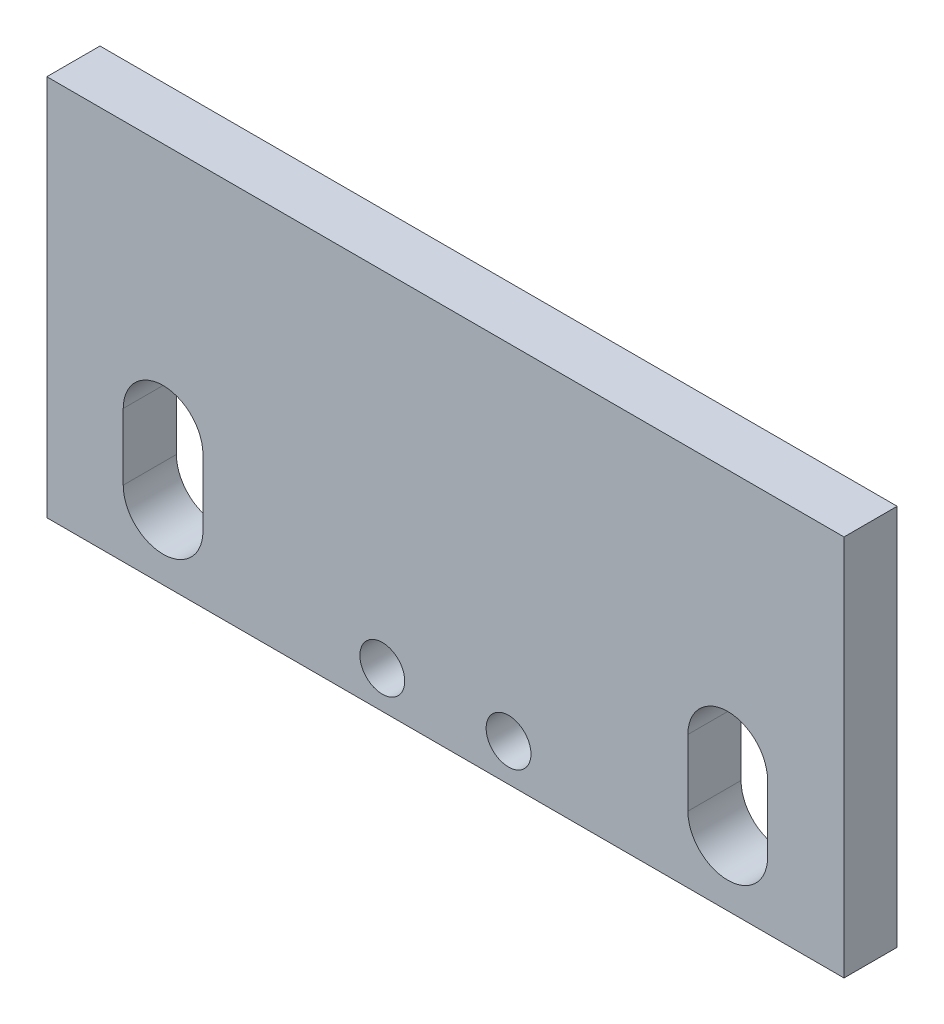
SolidWorks part; units mm, degrees
ref_plane "Front Plane" through (0, 0, 0) normal (0, 0, 1) x (1, 0, 0)
ref_plane "Top Plane" through (0, 0, 0) normal (0, 1, 0) x (1, 0, 0)
ref_plane "Right Plane" through (0, 0, 0) normal (1, 0, 0) x (0, 0, -1)
sketch "Sketch2" plane through (0, 0, 0) normal (0, 0, 1) x (1, 0, 0)
  line L0 (-0.0058, 0.0349) -> (7.9941, 0.0349) construction
  line L1 (7.9941, 0.0349) -> (7.9941, 12.5349) construction
  line L2 (-0.0058, 0.0349) -> (-0.0058, 12.5349) construction
  line L3 (-0.0058, 12.5349) -> (7.9941, 12.5349) construction
  line L4 (3.9941, 11.5349) -> (3.9941, 0.0349) construction
  line L5 (-8.0058, 11.5349) -> (15.9941, 11.5349)
  line L6 (-8.0058, 11.5349) -> (-8.0058, 0.0349)
  line L7 (-8.0058, 0.0349) -> (15.9941, 0.0349)
  line L8 (15.9941, 11.5349) -> (15.9941, 0.0349)
  line L9 (12.4941, 2.0349) -> (12.4941, 4.0349) construction
  line L10 (11.2941, 2.0349) -> (11.2941, 4.0349)
  line L11 (13.6941, 2.0349) -> (13.6941, 4.0349)
  line L12 (-4.5058, 2.0349) -> (-4.5058, 4.0349) construction
  line L13 (-3.3058, 2.0349) -> (-3.3058, 4.0349)
  line L14 (-5.7058, 2.0349) -> (-5.7058, 4.0349)
  circle A0 centre (6.1921, 5.5961) radius 0.1 construction
  circle A1 centre (3.4362, 3.6911) radius 0.1 construction
  circle A2 centre (0.8454, 4.2118) radius 0.1 construction
  circle A3 centre (0.8708, 9.4188) radius 0.1 construction
  circle A4 centre (7.3224, 11.0317) radius 0.1 construction
  circle A5 centre (0.7565, 11.0317) radius 0.1 construction
  circle A6 centre (1.6836, 7.4122) radius 0.1 construction
  circle A7 centre (6.6112, 10.3586) radius 0.1 construction
  circle A8 centre (0.8708, 10.1554) radius 0.1 construction
  circle A9 centre (2.0942, 1.1599) radius 0.675 construction
  circle A10 centre (5.8942, 1.1599) radius 0.675 construction
  circle A11 centre (-0.0055, 5.431) radius 0.3 construction
  circle A12 centre (-0.0055, 8.4282) radius 0.3 construction
  circle A13 centre (7.9955, 3.145) radius 0.3 construction
  circle A14 centre (7.9955, 5.1389) radius 0.3 construction
  circle A15 centre (7.9955, 8.1361) radius 0.3 construction
  circle A16 centre (7.9955, 9.6347) radius 0.3 construction
  circle A17 centre (7.9955, 6.6375) radius 0.3 construction
  circle A18 centre (-0.0055, 6.9296) radius 0.3 construction
  circle A19 centre (2.0942, 1.1599) radius 0.675 construction
  circle A20 centre (5.8942, 1.1599) radius 0.675 construction
  arc A22 (11.2941, 2.0349) -> (13.6941, 2.0349) centre (12.4941, 2.0349) ccw
  arc A23 (13.6941, 4.0349) -> (11.2941, 4.0349) centre (12.4941, 4.0349) ccw
  arc A24 (-3.3058, 2.0349) -> (-5.7058, 2.0349) centre (-4.5058, 2.0349) cw
  arc A25 (-5.7058, 4.0349) -> (-3.3058, 4.0349) centre (-4.5058, 4.0349) cw
  circle A26 centre (2.0942, 1.1599) radius 0.675
  circle A27 centre (5.8942, 1.1599) radius 0.675
  point P52 (12.4941, 3.0349)
  point P59 (-4.5058, 3.0349)
  dimension "D5" = 3.5
  dimension "D1" = 8
  dimension "D2" = 8
  dimension "D3" = 2.4
  dimension "D4" = 2
  dimension "D6" = 2
  dimension "D7" = 1
extrude "Boss-Extrude1" add sketch "Sketch2" along normal blind 1.6
ref_plane "Plane1" through (3.9941, 0, 0) normal (-1, 0, 0) x (0, 0, 1)
